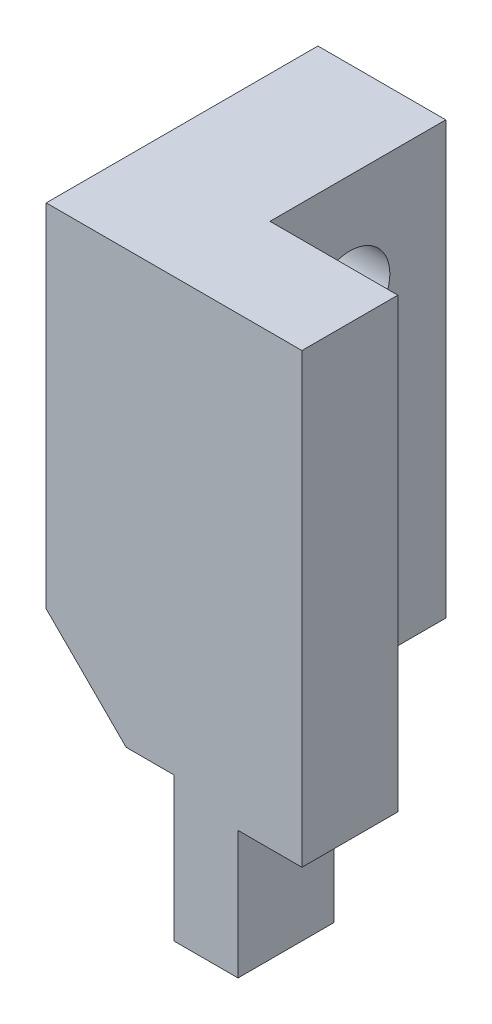
SolidWorks part; units mm, degrees
material "SKD11淬火HRC56-60"
ref_plane "前基準面" through (0, 0, 0) normal (0, 0, 1) x (1, 0, 0)
ref_plane "上基準面" through (0, 0, 0) normal (0, 1, 0) x (1, 0, 0)
ref_plane "右基準面" through (0, 0, 0) normal (1, 0, 0) x (0, 0, -1)
sketch "草图1" plane through (0, 0, 0) normal (0, 0, 1) x (1, 0, 0)
  line L1 (0, 0) -> (8, 0)
  line L2 (0, 0) -> (0, 18)
  line L3 (0, 18) -> (8, 18)
  line L4 (8, 0) -> (8, 18)
  dimension "D1" = 8
  dimension "D2" = 18
extrude "凸台-拉伸1" add sketch "草图1" along normal blind 8.5
sketch "草图2" plane through (0, 0, 8.5) normal (0, 0, 1) x (1, 0, 0)
  line L1 (8, 0) -> (6, 0)
  line L2 (8, 0) -> (8, 4)
  line L3 (8, 4) -> (6, 4)
  line L4 (6, 0) -> (6, 4)
  dimension "D1" = 4
  dimension "D2" = 2
extrude "切除-拉伸1" cut sketch "草图2" against normal through all
sketch "草图3" plane through (0, 18, 0) normal (0, 1, 0) x (1, 0, 0)
  line L0 (8, 0) -> (0, 0) construction
  line L1 (4, 0) -> (8, 0)
  line L2 (4, 0) -> (4, -5.5)
  line L3 (4, -5.5) -> (8, -5.5)
  line L4 (8, 0) -> (8, -5.5)
  line L5 (8, -8.5) -> (8, 0) construction
  dimension "D1" = 5.5
  dimension "D2" = 4
extrude "切除-拉伸2" cut sketch "草图3" against normal through all
sketch "草图4" plane through (4, 0, 0) normal (1, 0, 0) x (0, 0, -1)
  line L0 (-5.5, 0) -> (-5.5, 18) construction
  line L1 (0, 0) -> (-5.5, 0)
  line L2 (0, 0) -> (0, 4)
  line L3 (0, 4) -> (-5.5, 4)
  line L4 (-5.5, 0) -> (-5.5, 4)
  dimension "D1" = 4
extrude "切除-拉伸3" cut sketch "草图4" against normal blind 7
sketch "草图5" plane through (0, 0, 8.5) normal (0, 0, 1) x (1, 0, 0)
  line L0 (0, 0) -> (6, 0) construction
  line L1 (4, 0) -> (0, 0)
  line L2 (4, 0) -> (4, 4.5)
  line L3 (4, 4.5) -> (0, 4.5)
  line L4 (0, 0) -> (0, 4.5)
  line L5 (0, 18) -> (0, 0) construction
  line L6 (6, 4) -> (6, 0) construction
  dimension "D1" = 2
  dimension "D2" = 4.5
extrude "切除-拉伸4" cut sketch "草图5" against normal through all
chamfer "倒角1" distance 2.5 angle 45 1 edges at (0, 4.5, 4.25)
hole_wizard "M3 螺纹孔1" positions "草图7" profile "草图6" tap size "M3" standard "ISO" end condition through all
sketch "草图7" plane through (4, 0, 0) normal (1, 0, 0) x (0, 0, -1)
  point P0 (-3, 14.7)
  point P1 (-3, 9)
sketch "草图6" plane through (4, 14.7, 3) normal (0, 1, 0) x (0, 0, -1)
  line L0 (0, 0) -> (0, 4)
  line L1 (0, 4) -> (1.25, 4)
  line L2 (1.25, 4) -> (1.25, 0)
  line L5 (1.25, 0) -> (0, 0)
  line L11 (0, -6.35) -> (0, 107.95) construction
  dimension "通孔螺纹孔钻头直径" = 2.5
  dimension "通孔螺纹孔钻头深度" = 4
cosmetic thread "孔螺蚊线1" parameters "D2"=3
cosmetic thread "孔螺蚊线2" parameters "D2"=3
